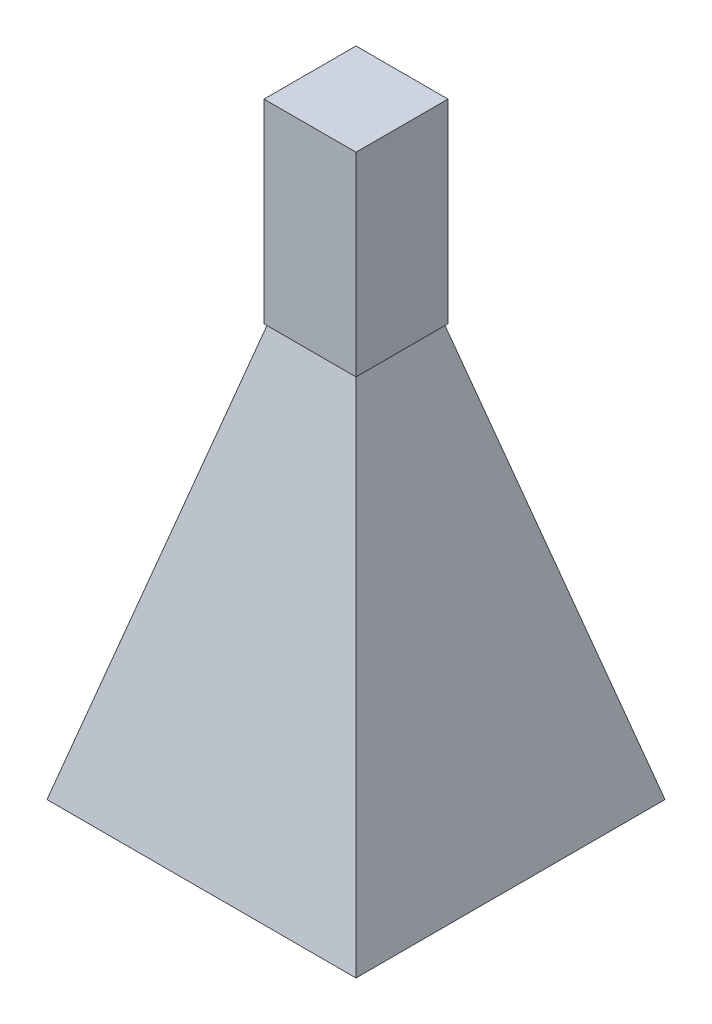
SolidWorks part; units mm, degrees
ref_plane "Front Plane" through (0, 0, 0) normal (0, 0, 1) x (1, 0, 0)
ref_plane "Top Plane" through (0, 0, 0) normal (0, 1, 0) x (1, 0, 0)
ref_plane "Right Plane" through (0, 0, 0) normal (1, 0, 0) x (0, 0, -1)
sketch "Sketch1" plane through (0, 0, 0) normal (0, 1, 0) x (1, 0, 0)
  line L1 (0, 0) -> (420, 0)
  line L2 (0, 0) -> (0, 420)
  line L3 (0, 420) -> (420, 420)
  line L4 (420, 0) -> (420, 420)
  point P5 (210, 210)
  dimension "D1" = 420
  dimension "D2" = 420
  dimension "D3" = 210
  dimension "D4" = 210
extrude "Boss-Extrude1" add sketch "Sketch1" along normal blind 784 draft 15 contours L2 L1 L4 L3
sketch "Sketch6" plane through (0, 0, 0) normal (0, -1, 0) x (1, 0, 0)
  line L8 (5, -415) -> (415, -415)
  line L9 (415, -415) -> (415, -5)
  line L10 (415, -5) -> (5, -5)
  line L11 (5, -5) -> (5, -415)
  line L12 (5, -415) -> (415, -415)
  line L13 (415, -415) -> (415, -5)
  line L14 (415, -5) -> (5, -5)
  line L15 (5, -5) -> (5, -415)
  dimension "D1" = 5
extrude "Cut-Extrude3" cut sketch "Sketch6" against normal blind 784 draft 15
ref_plane "Plane3" through (0, 560, 0) normal (0, 1, 0) x (1, 0, 0)
sketch "Sketch8" plane through (0, 560, 0) normal (0, 1, 0) x (1, 0, 0)
  line L1 (147.5, 147.5) -> (272.5, 147.5)
  line L2 (147.5, 147.5) -> (147.5, 272.5)
  line L3 (147.5, 272.5) -> (272.5, 272.5)
  line L4 (272.5, 147.5) -> (272.5, 272.5)
  line L5 (147.5, 147.5) -> (272.5, 272.5) construction
  line L6 (147.5, 272.5) -> (272.5, 147.5) construction
  point P0 (210, 210)
  dimension "D1" = 125
  dimension "D2" = 125
extrude "Boss-Extrude2" add sketch "Sketch8" along normal blind 264.49
sketch "Sketch9" plane through (0, 560, 0) normal (0, -1, 0) x (1, 0, 0)
  line L8 (165.0515, -165.0515) -> (165.0515, -254.9485)
  line L9 (165.0515, -254.9485) -> (254.9485, -254.9485)
  line L10 (254.9485, -254.9485) -> (254.9485, -165.0515)
  line L11 (254.9485, -165.0515) -> (165.0515, -165.0515)
  line L12 (165.0515, -165.0515) -> (165.0515, -254.9485)
  line L13 (165.0515, -254.9485) -> (254.9485, -254.9485)
  line L14 (254.9485, -254.9485) -> (254.9485, -165.0515)
  line L15 (254.9485, -165.0515) -> (165.0515, -165.0515)
  dimension "D1" = 10
extrude "Cut-Extrude4" cut sketch "Sketch9" against normal blind 248.49
sketch "Sketch10" plane through (0, 0, -272.5) normal (0, 0, -1) x (-1, 0, 0)
  line L0 (0, 0) -> (-420, 0) construction
  line L1 (-272.5, 824.49) -> (-272.5, 560) construction
  circle A0 centre (-210, 784) radius 10
  dimension "D1" = 20
  dimension "D2" = 784
  dimension "D3" = 62.5
extrude "Cut-Extrude5" cut sketch "Sketch10" against normal blind 32.49
